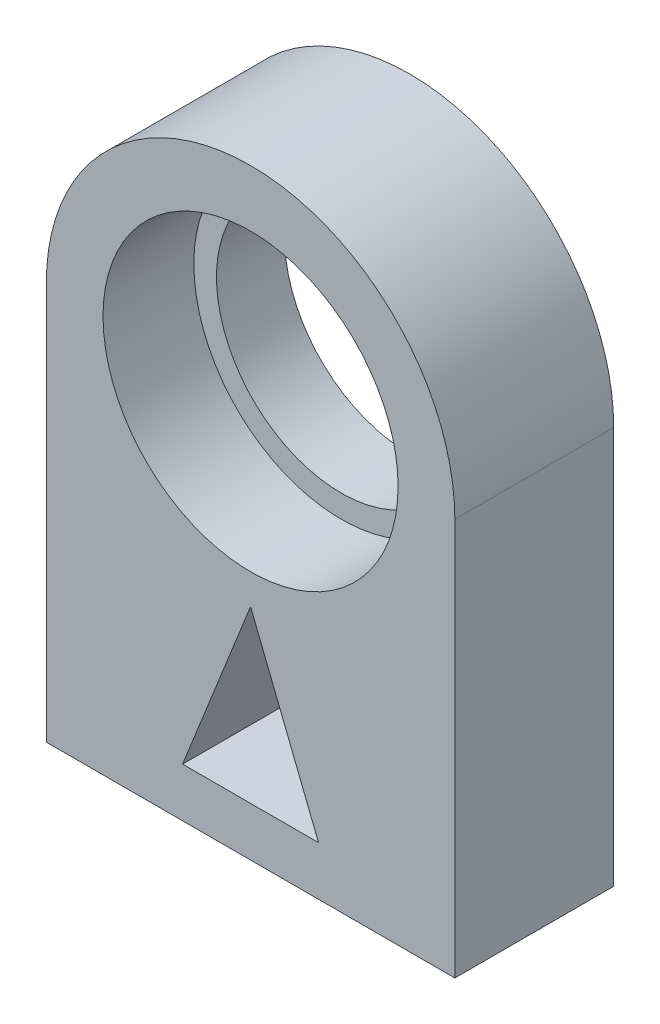
SolidWorks part; units mm, degrees
material "PBT General Purpose"
ref_plane "Front Plane" through (0, 0, 0) normal (0, 0, 1) x (1, 0, 0)
ref_plane "Top Plane" through (0, 0, 0) normal (0, 1, 0) x (1, 0, 0)
ref_plane "Right Plane" through (0, 0, 0) normal (1, 0, 0) x (0, 0, -1)
sketch "Sketch1" plane through (0, 0, 0) normal (0, 0, 1) x (1, 0, 0)
  line L1 (0, 0) -> (18, 0)
  line L2 (0, 0) -> (0, 18)
  line L3 (0, 18) -> (18, 18)
  line L4 (18, 0) -> (18, 18)
  circle A0 centre (9, 18) radius 9
  circle A1 centre (9, 18) radius 5.5
  dimension "D3" = 18
  dimension "D4" = 11
  dimension "D1" = 18
  dimension "D2" = 18
extrude "Boss-Extrude1" add sketch "Sketch1" along normal blind 7 contours A1 L3 A0 | A1 L3 A0 | A0 L2 L1 L4
sketch "Sketch2" plane through (0, 0, 0) normal (0, -1, 0) x (1, 0, 0)
  line L0 (18, 7) -> (18, 0) construction
  line L1 (0, 7) -> (0, 0) construction
  circle A0 centre (15, 3.5) radius 1.25
  circle A1 centre (3, 3.5) radius 1.25
  point P0 (15, 3.5)
  dimension "D2" = 2.5
  dimension "D4" = 2.5
  dimension "D1" = 3
  dimension "D3" = 3
extrude "Cut-Extrude1" cut sketch "Sketch2" against normal blind 12
cosmetic thread "Cosmetic Thread1" parameters "D2"=3
cosmetic thread "Cosmetic Thread2" parameters "D2"=3
sketch "Sketch3" plane through (0, 0, 7) normal (0, 0, 1) x (1, 0, 0)
  circle A0 centre (9, 18) radius 6.5
  dimension "D1" = 13
extrude "Cut-Extrude2" cut sketch "Sketch3" against normal blind 4
sketch "Sketch4" plane through (0, 0, 0) normal (0, -1, 0) x (1, 0, 0)
  line L1 (18, 0) -> (0, 0)
  line L2 (18, 0) -> (18, 7)
  line L3 (18, 7) -> (0, 7)
  line L4 (0, 0) -> (0, 7)
extrude "Cut-Extrude3" cut sketch "Sketch4" against normal blind 0.5
sketch "Sketch5" plane through (0, 0, 0) normal (0, 0, -1) x (-1, 0, 0)
  line L0 (-11.9954, 2.6629) -> (-9, 10.1702)
  line L1 (-11.9954, 10.1702) -> (-6.0046, 10.1702)
  line L2 (-11.9954, 10.1702) -> (-11.9954, 2.6629)
  line L3 (-11.9954, 2.6629) -> (-6.0046, 2.6629)
  line L4 (-6.0046, 10.1702) -> (-6.0046, 2.6629)
  line L5 (-11.9954, 10.1702) -> (-6.0046, 2.6629) construction
  line L6 (-11.9954, 2.6629) -> (-6.0046, 10.1702) construction
  line L7 (-9, 10.1702) -> (-6.0046, 2.6629)
  point P0 (-9, 6.4166)
extrude "Cut-Extrude5" cut sketch "Sketch5" against normal blind 10 contours L7 L0 L3
